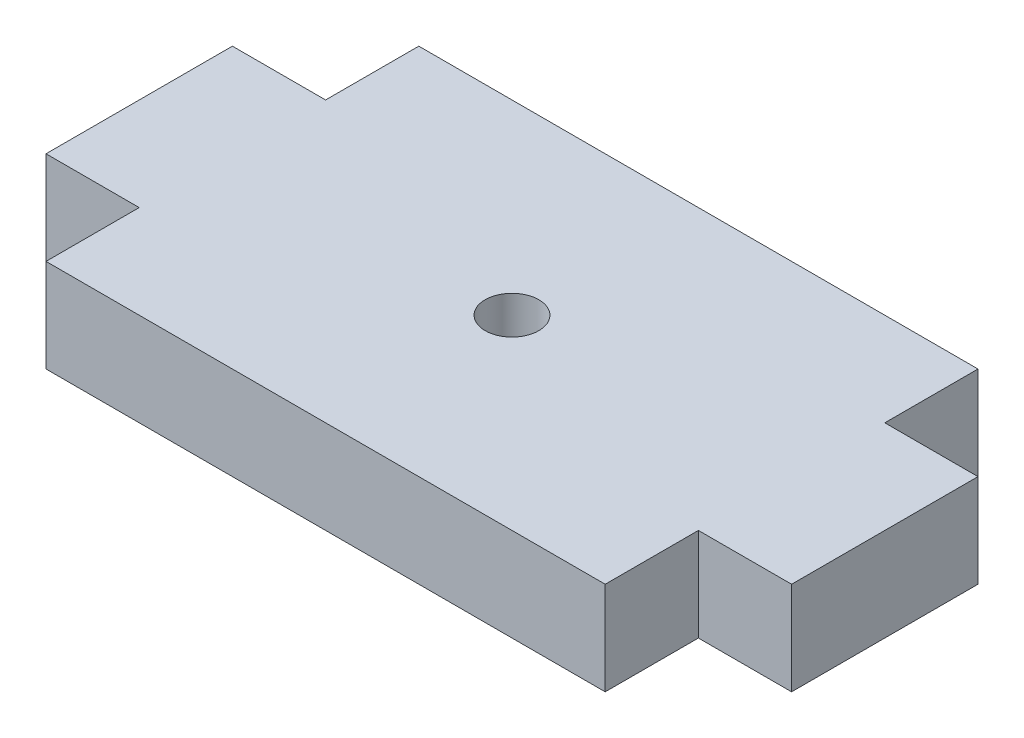
SolidWorks part; units mm, degrees
ref_plane "Front Plane" through (0, 0, 0) normal (0, 0, 1) x (1, 0, 0)
ref_plane "Top Plane" through (0, 0, 0) normal (0, 1, 0) x (1, 0, 0)
ref_plane "Right Plane" through (0, 0, 0) normal (1, 0, 0) x (0, 0, -1)
sketch "Sketch1" plane through (0, 0, 0) normal (0, 1, 0) x (1, 0, 0)
  line L0 (0, 0) -> (38.1, -25.4) construction
  line L1 (0, 0) -> (38.1, 0)
  line L2 (0, 0) -> (0, -25.4)
  line L3 (0, -25.4) -> (38.1, -25.4)
  line L4 (38.1, 0) -> (38.1, -25.4)
  line L5 (0, -12.7) -> (38.1, -12.7) construction
  line L6 (0, -12.7) -> (-6.35, -12.7) construction
  line L7 (38.1, -19.05) -> (44.45, -19.05)
  line L8 (38.1, -19.05) -> (38.1, -6.35)
  line L9 (38.1, -6.35) -> (44.45, -6.35)
  line L10 (44.45, -19.05) -> (44.45, -6.35)
  line L11 (0, -6.35) -> (-6.35, -6.35)
  line L12 (0, -6.35) -> (0, -19.05)
  line L13 (0, -19.05) -> (-6.35, -19.05)
  line L14 (-6.35, -6.35) -> (-6.35, -19.05)
  line L15 (38.1, -12.7) -> (44.45, -12.7) construction
  circle A0 centre (19.05, -12.7) radius 1.8288
  point P17 (-6.0942, -9.9441)
  dimension "D3" = 3.6576
  dimension "D1" = 25.4
  dimension "D2" = 38.1
  dimension "D4" = 6.35
  dimension "D5" = 12.7
extrude "Boss-Extrude1" add sketch "Sketch1" along normal blind 6.35 contours L4 L1 L2 L3 A0 | L7 L10 L9 L4 | L11 L14 L13 L2
